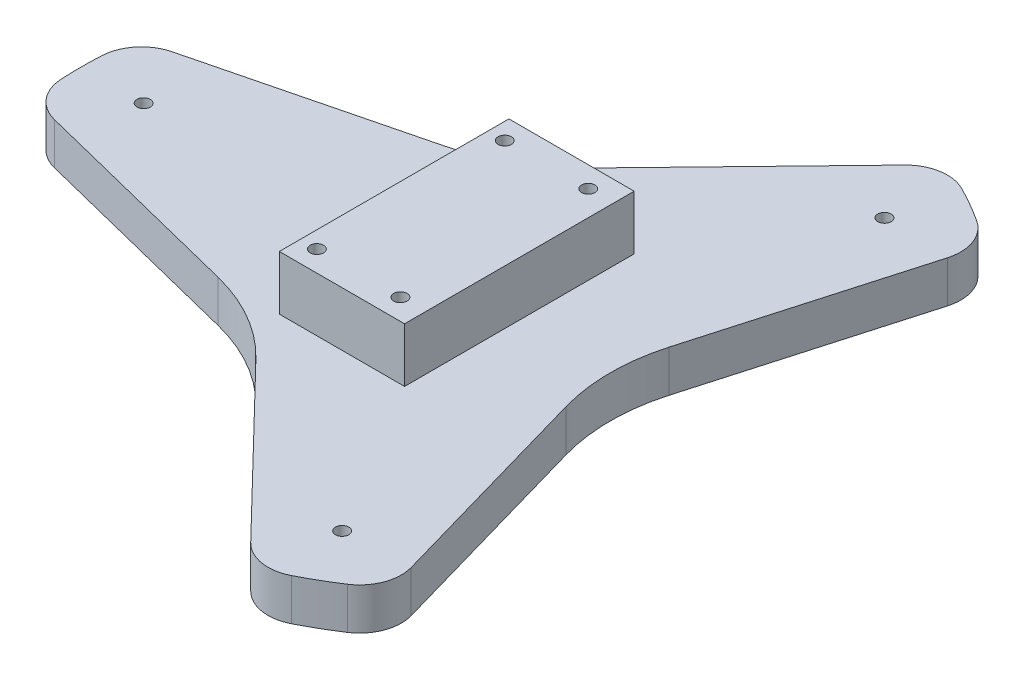
SolidWorks part; units mm, degrees
ref_plane "Front Plane" through (0, 0, 0) normal (0, 0, 1) x (1, 0, 0)
ref_plane "Top Plane" through (0, 0, 0) normal (0, 1, 0) x (1, 0, 0)
ref_plane "Right Plane" through (0, 0, 0) normal (1, 0, 0) x (0, 0, -1)
sketch "Sketch1" plane through (0, 0, 0) normal (0, 1, 0) x (1, 0, 0)
  line L0 (-89.1472, 12.3603) -> (-17.5, 30.3109)
  line L4 (-17.5, 30.3109) -> (33.8693, 83.3839)
  line L8 (55.2779, 71.0236) -> (35, 0)
  line L9 (35, 0) -> (55.2779, -71.0236)
  line L10 (-17.5, 30.3109) -> (-17.5, -30.3109)
  line L11 (33.8693, -83.3839) -> (-17.5, -30.3109)
  line L12 (-17.5, -30.3109) -> (-89.1472, -12.3603)
  line L14 (35, 0) -> (-17.5, 30.3109)
  line L16 (-17.5, -30.3109) -> (35, 0)
  arc A0 (-89.1472, 12.3603) -> (-89.1472, -12.3603) centre (0, 0) ccw
  circle A1 centre (-75, 0) radius 1.6
  circle A2 centre (37.5, 64.9519) radius 1.6
  circle A3 centre (37.5, -64.9519) radius 1.6
  arc A4 (55.2779, 71.0236) -> (33.8693, 83.3839) centre (0, 0) ccw
  arc A5 (33.8693, -83.3839) -> (55.2779, -71.0236) centre (0, 0) ccw
  circle A6 centre (9, 22.5) radius 1.6
  circle A7 centre (-11, 22.5) radius 1.6
  circle A8 centre (9, -22.5) radius 1.6
  circle A9 centre (-11, -22.5) radius 1.6
  circle A10 centre (0, 0) radius 35
  point P12 (0, 0)
  point P25 (0, 0)
  dimension "D1" = 75
  dimension "D3" = 180
  dimension "D4" = 3.2
  dimension "D16" = 3.2
  dimension "D9" = 22.5
  dimension "D5" = 70
  dimension "D12" = 45
  dimension "D13" = 20
  dimension "D14" = 9
  dimension "D2" = 3
extrude "Boss-Extrude1" add sketch "Sketch1" along normal blind 10 contours A10 L0 A0 L12 A1 | L10 L16 L14 A9 A7 | L10 A10 | L14 A10 A6 | A10 L8 A4 L4 A2 | L16 A10 A8 | A10 L11 A5 L9 A3
sketch "Sketch2" plane through (0, 10, 0) normal (0, 1, 0) x (1, 0, 0)
  line L0 (54.5753, 69.5272) -> (32.9247, 82.0272)
  line L1 (-87.5, 12.5) -> (-62.5, 12.5)
  line L2 (-87.5, 12.5) -> (-87.5, -12.5)
  line L3 (-87.5, -12.5) -> (-62.5, -12.5)
  line L4 (-62.5, 12.5) -> (-62.5, -12.5)
  line L5 (-85, 8) -> (-65, 8)
  line L6 (-85, 8) -> (-85, 7.5)
  line L7 (-85, 7.5) -> (-65, 7.5)
  line L8 (-65, 8) -> (-65, 7.5)
  line L9 (-85, -7.5) -> (-65, -7.5)
  line L10 (-85, -7.5) -> (-85, -8)
  line L11 (-85, -8) -> (-65, -8)
  line L12 (-65, -7.5) -> (-65, -8)
  line L13 (54.5753, 69.5272) -> (42.0753, 47.8766)
  line L14 (49.4282, 69.6122) -> (39.4282, 52.2917)
  line L15 (48.9952, 69.8622) -> (38.9952, 52.5417)
  line L16 (42.0753, 47.8766) -> (20.4247, 60.3766)
  line L17 (32.9247, 82.0272) -> (20.4247, 60.3766)
  line L18 (36.0048, 77.3622) -> (26.0048, 60.0417)
  line L19 (35.5718, 77.6122) -> (25.5718, 60.2917)
  line L20 (26.0048, 60.0417) -> (25.5718, 60.2917)
  line L21 (36.0048, 77.3622) -> (35.5718, 77.6122)
  line L22 (49.4282, 69.6122) -> (48.9952, 69.8622)
  line L23 (39.4282, 52.2917) -> (38.9952, 52.5417)
  line L24 (32.9247, -82.0272) -> (54.5753, -69.5272)
  line L25 (32.9247, -82.0272) -> (20.4247, -60.3766)
  line L26 (35.5718, -77.6122) -> (25.5718, -60.2917)
  line L27 (36.0048, -77.3622) -> (26.0048, -60.0417)
  line L28 (20.4247, -60.3766) -> (42.0753, -47.8766)
  line L29 (54.5753, -69.5272) -> (42.0753, -47.8766)
  line L30 (48.9952, -69.8622) -> (38.9952, -52.5417)
  line L31 (49.4282, -69.6122) -> (39.4282, -52.2917)
  line L32 (38.9952, -52.5417) -> (39.4282, -52.2917)
  line L33 (48.9952, -69.8622) -> (49.4282, -69.6122)
  line L34 (35.5718, -77.6122) -> (36.0048, -77.3622)
  line L35 (25.5718, -60.2917) -> (26.0048, -60.0417)
  line L48 (0, 0) -> (-62.5, 12.5) construction
  circle A0 centre (-75, 0) radius 1.6
  circle A2 centre (37.5, 64.9519) radius 1.6
  circle A3 centre (37.5, -64.9519) radius 1.6
  point P62 (0, 0)
  dimension "D11" = 3.2
  dimension "D1" = 25
  dimension "D2" = 25
  dimension "D3" = 20
  dimension "D4" = 0.5
  dimension "D5" = 0.5
  dimension "D6" = 2.5
  dimension "D7" = 15
  dimension "D8" = 4.5
  dimension "D9" = 12.5
  dimension "D10" = 12.5
  dimension "D13" = 63.7377
  dimension "D12" = 3
extrude "Boss-Extrude2" [suppressed] add sketch "Sketch2" along normal blind 10
fillet "Fillet1" radius 10 6 edges at (33.8693, 5, -83.3839) (-89.1472, 5, -12.3603) (55.2779, 5, -71.0236) (55.2779, 5, 71.0236) (33.8693, 5, 83.3839) (-89.1472, 5, 12.3603)
fillet "Fillet2" radius 45 3 edges at (-17.5, 5, 30.3109) (-17.5, 5, -30.3109) (35, 5, 0)
sketch "Sketch3" plane through (0, 10, 0) normal (0, 1, 0) x (1, 0, 0)
  line L1 (-15, 27.5) -> (15, 27.5)
  line L2 (-15, 27.5) -> (-15, -27.5)
  line L3 (-15, -27.5) -> (15, -27.5)
  line L4 (15, 27.5) -> (15, -27.5)
  circle A0 centre (-11, 22.5) radius 1.6
  circle A1 centre (9, 22.5) radius 1.6
  circle A2 centre (-11, -22.5) radius 1.6
  circle A3 centre (9, -22.5) radius 1.6
  dimension "D5" = 3.2
  dimension "D1" = 55
  dimension "D2" = 30
  dimension "D3" = 27.5
  dimension "D4" = 15
  dimension "D6" = 20
  dimension "D7" = 45
  dimension "D8" = 9
  dimension "D9" = 22.5
extrude "Boss-Extrude3" add sketch "Sketch3" along normal blind 13 separate body
sketch "Sketch4" plane through (0, 0, 0) normal (0, -1, 0) x (1, 0, 0)
  circle A0 centre (-11, 22.5) radius 5
  circle A1 centre (9, 22.5) radius 5
  circle A2 centre (9, -22.5) radius 5
  circle A3 centre (-11, -22.5) radius 5
  circle A4 centre (-75, 0) radius 5
  circle A5 centre (37.5, -64.9519) radius 5
  circle A6 centre (37.5, 64.9519) radius 5
  dimension "D1" = 10
extrude "Cut-Extrude1" cut sketch "Sketch4" against normal blind 5
